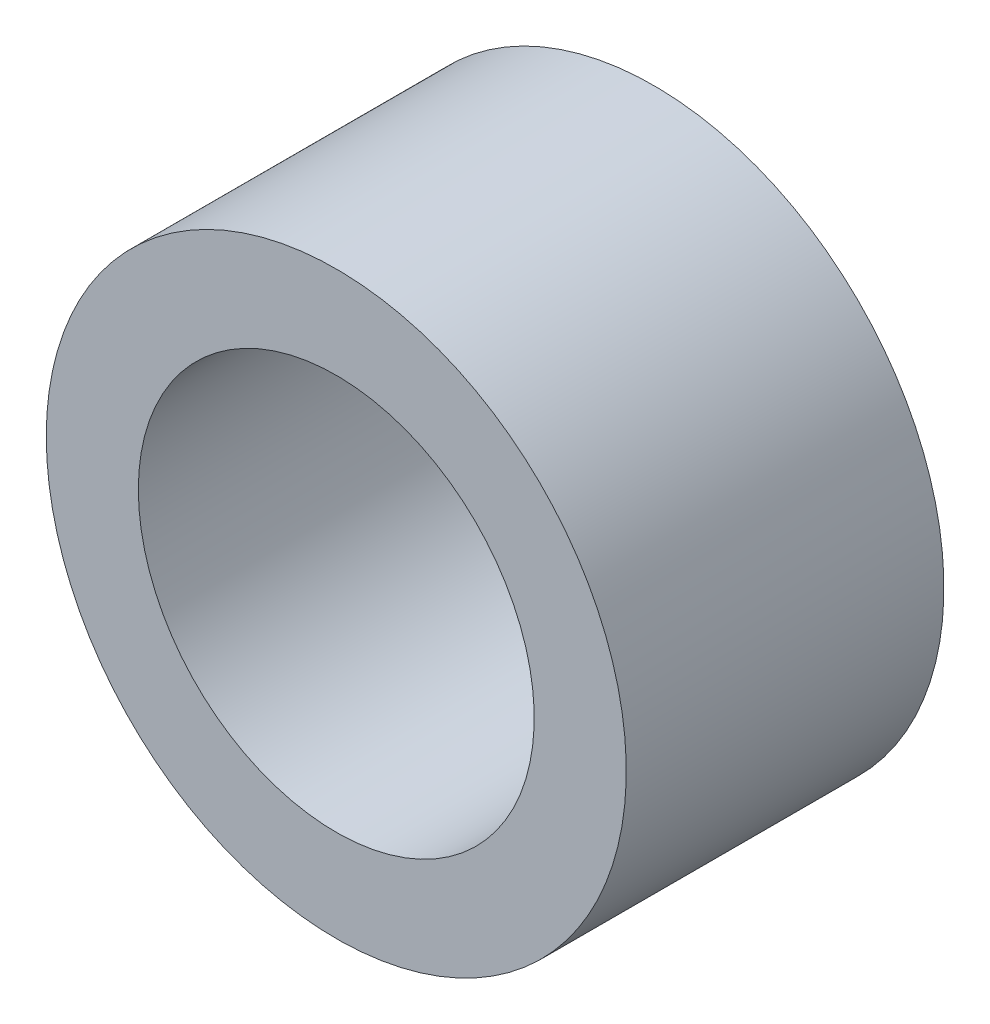
SolidWorks part; units mm, degrees
ref_plane "Front Plane" through (0, 0, 0) normal (0, 0, 1) x (1, 0, 0)
ref_plane "Top Plane" through (0, 0, 0) normal (0, 1, 0) x (1, 0, 0)
ref_plane "Right Plane" through (0, 0, 0) normal (1, 0, 0) x (0, 0, -1)
sketch "Sketch1" plane through (0, 0, 0) normal (0, 0, 1) x (1, 0, 0)
  circle A0 centre (0, 0) radius 3.15
  circle A1 centre (0, 0) radius 2.15
  dimension "D1" = 6.3
  dimension "D2" = 4.3
extrude "Boss-Extrude1" add sketch "Sketch1" along normal blind 3.45
